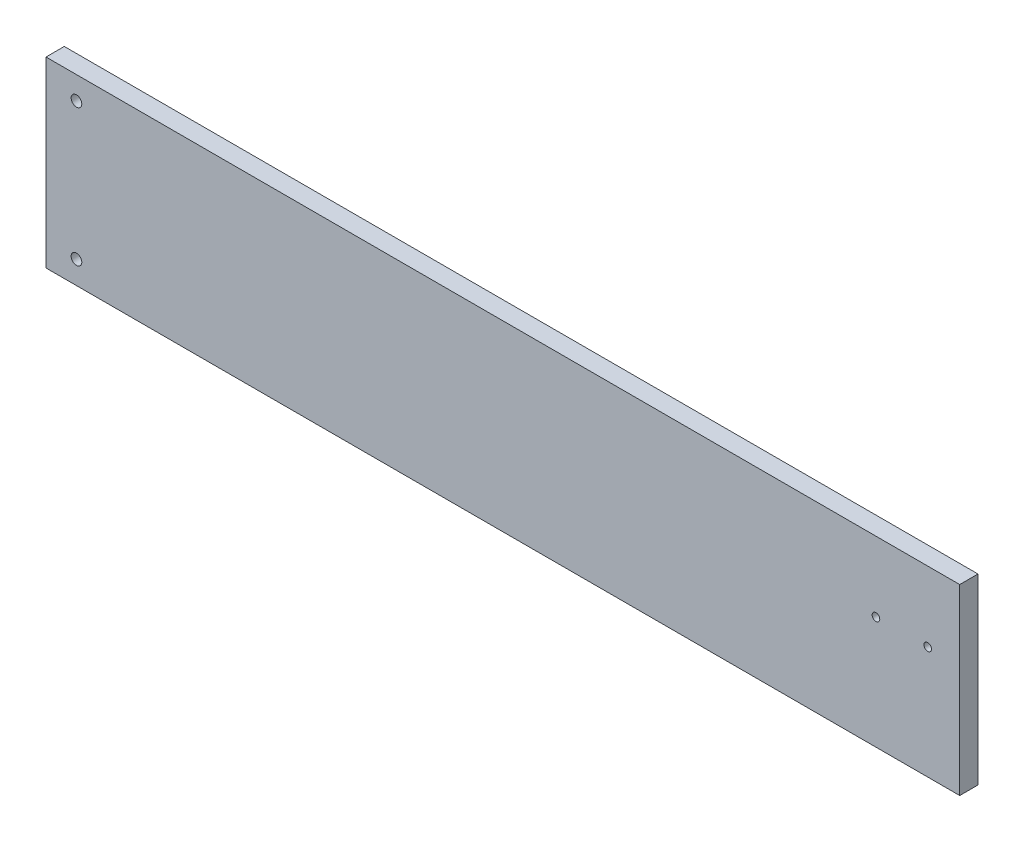
SolidWorks part; units mm, degrees
material "铝材"
ref_plane "前基準面" through (0, 0, 0) normal (0, 0, 1) x (1, 0, 0)
ref_plane "上基準面" through (0, 0, 0) normal (0, 1, 0) x (1, 0, 0)
ref_plane "右基準面" through (0, 0, 0) normal (1, 0, 0) x (0, 0, -1)
sketch "草图1" plane through (0, 0, 0) normal (0, 0, 1) x (1, 0, 0)
  line L1 (0, 0) -> (600, 0)
  line L2 (0, 0) -> (0, 120)
  line L3 (0, 120) -> (600, 120)
  line L4 (600, 0) -> (600, 120)
  dimension "D1" = 120
  dimension "D2" = 600
extrude "凸台-拉伸1" add sketch "草图1" along normal blind 12
sketch "草图4" plane through (0, 0, 0) normal (0, 0, -1) x (-1, 0, 0)
  line L0 (0, 60) -> (-71.8393, 60) construction
  line L1 (0, 120) -> (0, 0) construction
  circle A0 centre (-20, 15) radius 3.5
  circle A1 centre (-20, 105) radius 3.5
  dimension "D1" = 7
  dimension "D2" = 90
  dimension "D3" = 20
extrude "切除-拉伸1" cut sketch "草图4" against normal through all
hole_wizard "M6 螺纹孔1" positions "草图6" profile "草图5" tap size "M6" standard "ISO" end condition through all
sketch "草图6" plane through (0, 0, 0) normal (0, 0, -1) x (-1, 0, 0)
  point P0 (-579, 74)
  point P1 (-545, 74)
sketch "草图5" plane through (579, 74, 0) normal (1, 0, 0) x (0, 1, 0)
  line L0 (0, 0) -> (0, 12)
  line L1 (0, 12) -> (2.5, 12)
  line L2 (2.5, 12) -> (2.5, 0)
  line L5 (2.5, 0) -> (0, 0)
  line L11 (0, -6.35) -> (0, 107.95) construction
  dimension "通孔螺纹孔钻头直径" = 5
  dimension "通孔螺纹孔钻头深度" = 12
cosmetic thread "孔螺蚊线1" parameters "D2"=6
cosmetic thread "孔螺蚊线2" parameters "D2"=6
